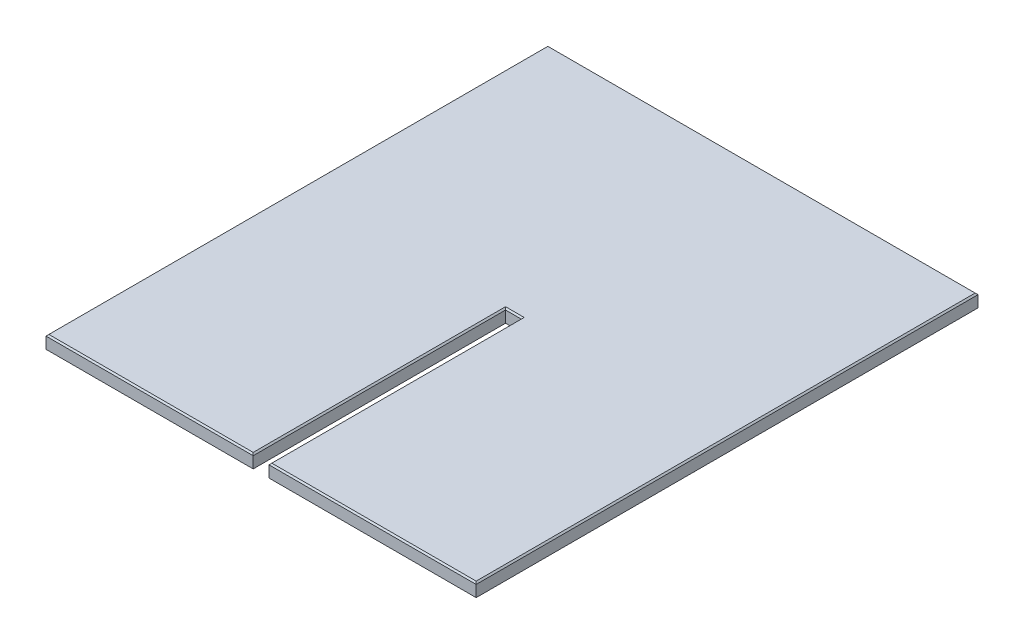
SolidWorks part; units mm, degrees
ref_plane "Front Plane" through (0, 0, 0) normal (0, 0, 1) x (1, 0, 0)
ref_plane "Top Plane" through (0, 0, 0) normal (0, 1, 0) x (1, 0, 0)
ref_plane "Right Plane" through (0, 0, 0) normal (1, 0, 0) x (0, 0, -1)
sketch "Sketch1" plane through (0, 0, 0) normal (0, 1, 0) x (1, 0, 0)
  line L0 (38.1, 44.45) -> (-38.1, -44.45) construction
  line L1 (-38.1, -44.45) -> (38.1, -44.45)
  line L2 (-38.1, -44.45) -> (-38.1, 44.45)
  line L3 (-38.1, 44.45) -> (38.1, 44.45)
  line L4 (38.1, -44.45) -> (38.1, 44.45)
  dimension "D1" = 76.2
  dimension "D2" = 88.9
extrude "Boss-Extrude1" add sketch "Sketch1" along normal mid plane 2.54
sketch "Sketch3" plane through (0, 1.27, 0) normal (0, 1, 0) x (1, 0, 0)
  line L0 (0, 0.254) -> (0, -44.45)
  line L1 (-38.1, -44.45) -> (38.1, -44.45) construction
  point P5 (0, 0)
  point P6 (0, 0.709)
  dimension "D1" = 0.254
extrude "Cut-Extrude-Thin1" cut sketch "Sketch3" against normal blind 2.794 and the other way through all thin thin type mid plane wall 2.794
chamfer "Chamfer1" distance 0.254 angle 45 16 edges at (1.397, -1.27, 22.098) (19.7485, -1.27, 44.45) (38.1, -1.27, 0) (0, -1.27, -44.45) (-38.1, -1.27, 0) (-19.7485, -1.27, 44.45) (-1.397, -1.27, 22.098) (0, -1.27, -0.254) (-19.7485, 1.27, 44.45) (-38.1, 1.27, 0) (0, 1.27, -44.45) (38.1, 1.27, 0) (19.7485, 1.27, 44.45) (1.397, 1.27, 22.098) (0, 1.27, -0.254) (-1.397, 1.27, 22.098)
